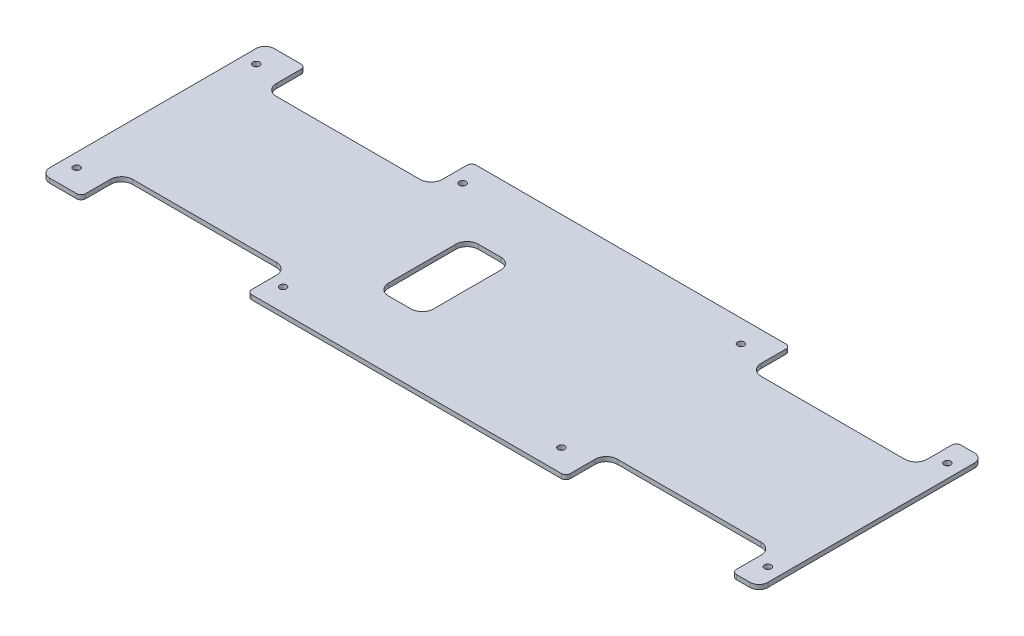
SolidWorks part; units mm, degrees
ref_plane "前视基准面" through (0, 0, 0) normal (0, 0, 1) x (1, 0, 0)
ref_plane "上视基准面" through (0, 0, 0) normal (0, 1, 0) x (1, 0, 0)
ref_plane "右视基准面" through (0, 0, 0) normal (1, 0, 0) x (0, 0, -1)
sketch "草图1" plane through (0, 0, 0) normal (0, 1, 0) x (1, 0, 0)
  line L0 (0, 0) -> (361.2231, 0) construction
  line L1 (0, -50) -> (0, 50)
  line L2 (0, 50) -> (18, 50)
  line L3 (18, 50) -> (18, 32)
  line L4 (18, 32) -> (92, 32)
  line L5 (92, 32) -> (92, 50)
  line L6 (92, 50) -> (234, 50)
  line L7 (234, 50) -> (234, 32)
  line L8 (234, 32) -> (308, 32)
  line L9 (308, 32) -> (308, 50)
  line L10 (308, 50) -> (320, 50)
  line L11 (320, 50) -> (320, -50)
  line L12 (308, -50) -> (320, -50)
  line L13 (308, -32) -> (308, -50)
  line L14 (234, -32) -> (308, -32)
  line L15 (234, -50) -> (234, -32)
  line L16 (92, -50) -> (234, -50)
  line L17 (92, -32) -> (92, -50)
  line L18 (18, -32) -> (92, -32)
  line L19 (18, -50) -> (18, -32)
  line L20 (0, -50) -> (18, -50)
  line L22 (120, -20) -> (140, -20)
  line L23 (120, -20) -> (120, 20)
  line L24 (120, 20) -> (140, 20)
  line L25 (140, -20) -> (140, 20)
  line L26 (120, -20) -> (140, 20) construction
  line L27 (120, 20) -> (140, -20) construction
  circle A0 centre (6, 40) radius 1.5
  circle A1 centre (98, 40) radius 1.5
  circle A2 centre (222, 40) radius 1.5
  circle A3 centre (314, 40) radius 1.5
  circle A4 centre (314, -40) radius 1.5
  circle A5 centre (222, -40) radius 1.5
  circle A6 centre (98, -40) radius 1.5
  circle A7 centre (6, -40) radius 1.5
  point P32 (320, 0)
  point P41 (130, 0)
  dimension "D7" = 6
  dimension "D8" = 6
  dimension "D9" = 12
  dimension "D10" = 6
  dimension "D11" = 10
  dimension "D13" = 3
  dimension "D1" = 18
  dimension "D2" = 74
  dimension "D3" = 142
  dimension "D4" = 74
  dimension "D5" = 12
  dimension "D6" = 100
  dimension "D12" = 18
  dimension "D14" = 20
  dimension "D15" = 40
  dimension "D16" = 28
extrude "凸台-拉伸1" add sketch "草图1" along normal blind 2
fillet "圆角1" radius 4 4 edges at (320, 1, -50) (320, 1, 50) (0, 1, -50) (0, 1, 50)
fillet "圆角2" radius 2 8 edges at (308, 1, -50) (308, 1, 50) (234, 1, -50) (234, 1, 50) (92, 1, -50) (92, 1, 50) (18, 1, -50) (18, 1, 50)
fillet "圆角3" radius 5 12 edges at (120, 1, -20) (140, 1, -20) (120, 1, 20) (140, 1, 20) (18, 1, -32) (92, 1, -32) (234, 1, -32) (308, 1, -32) (308, 1, 32) (234, 1, 32) (92, 1, 32) (18, 1, 32)
